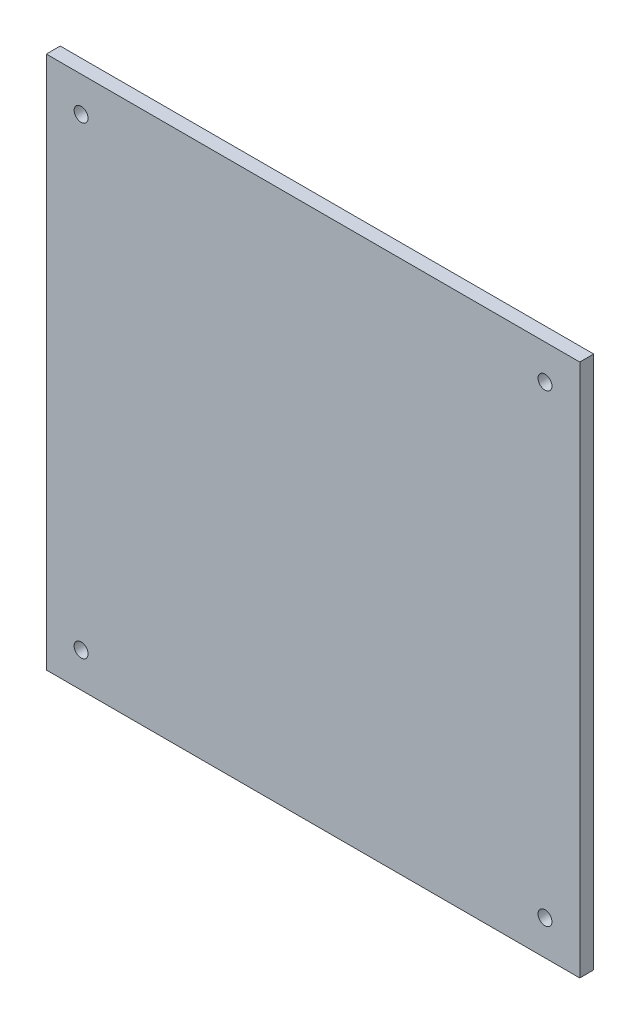
SolidWorks part; units mm, degrees
ref_plane "Front" through (0, 0, 0) normal (0, 0, 1) x (1, 0, 0)
ref_plane "Top" through (0, 0, 0) normal (0, 1, 0) x (1, 0, 0)
ref_plane "Right" through (0, 0, 0) normal (1, 0, 0) x (0, 0, -1)
sketch "Sketch1" plane through (0, 0, 0) normal (0, 0, 1) x (1, 0, 0)
  line L1 (-57.5, -57.5) -> (57.5, -57.5)
  line L2 (-57.5, -57.5) -> (-57.5, 57.5)
  line L3 (-57.5, 57.5) -> (57.5, 57.5)
  line L4 (57.5, -57.5) -> (57.5, 57.5)
  line L5 (-57.5, -57.5) -> (57.5, 57.5) construction
  line L6 (-57.5, 57.5) -> (57.5, -57.5) construction
  circle A0 centre (-50, 50) radius 1.5
  circle A1 centre (50, 50) radius 1.5
  circle A2 centre (-50, -50) radius 1.5
  circle A3 centre (50, -50) radius 1.5
  point P8 (0, 0)
  dimension "D1" = 100
  dimension "D10" = 3
  dimension "D11" = 3
  dimension "D12" = 3
  dimension "D13" = 3
  dimension "D2" = 100
  dimension "D3" = 100
  dimension "D4" = 100
  dimension "D5" = 50
  dimension "D6" = 50
  dimension "D7" = 50
  dimension "D8" = 115
  dimension "D9" = 115
extrude "Boss-Extrude1" add sketch "Sketch1" along normal blind 3
